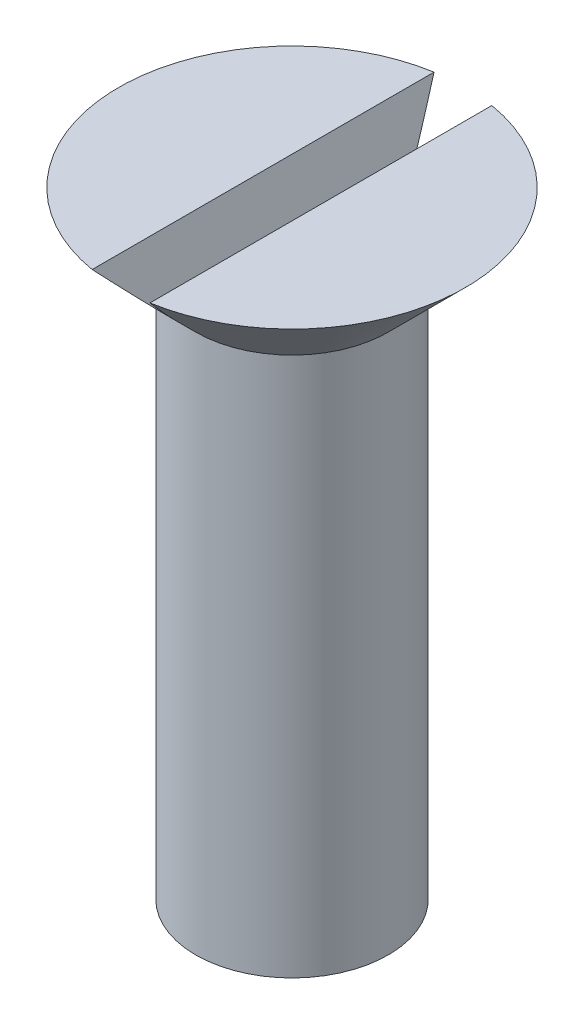
SolidWorks part; units mm, degrees
ref_plane "Front Plane" through (0, 0, 0) normal (0, 0, 1) x (1, 0, 0)
ref_plane "Top Plane" through (0, 0, 0) normal (0, 1, 0) x (1, 0, 0)
ref_plane "Right Plane" through (0, 0, 0) normal (1, 0, 0) x (0, 0, -1)
sketch "Sketch1" plane through (0, 0, 0) normal (0, 0, 1) x (1, 0, 0)
  line L0 (0, 84.5392) -> (0, -57.0407) construction
  line L1 (0, 3.781) -> (4.5, 3.781)
  line L2 (4.5, 3.781) -> (2.5, 1.781)
  line L3 (2.5, 1.781) -> (2.5, -12.219)
  line L4 (2.5, -12.219) -> (0, -12.219)
  line L5 (0, 3.781) -> (0, -12.219)
  dimension "D1" = 14
  dimension "D2" = 4.5
  dimension "D3" = 5
  dimension "D4" = 135
revolve "Revolve1" add sketch "Sketch1" angle 360 about L0
sketch "Sketch2" plane through (0, 0, 0) normal (0, 0, 1) x (1, 0, 0)
  line L0 (0, 0) -> (0, 7.1962) construction
  line L1 (-0.75, 3.781) -> (0, 2.281)
  line L2 (4.5, 3.781) -> (-4.5, 3.781) construction
  line L3 (0, 2.281) -> (0.75, 3.781)
  line L4 (0.75, 3.781) -> (-0.75, 3.781)
  dimension "D1" = 1.5
  dimension "D2" = 1.5
  dimension "D3" = 0.75
extrude "Extrude1" cut sketch "Sketch2" against normal mid plane 10
